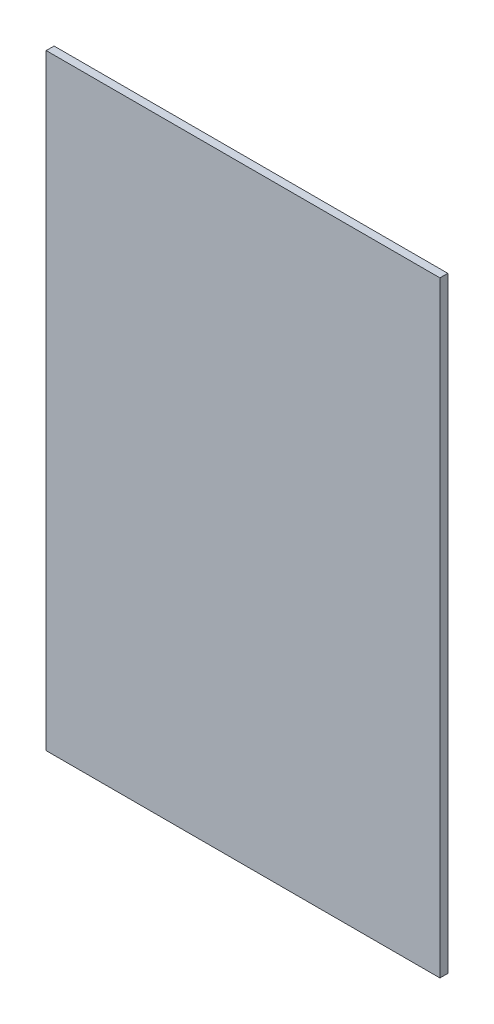
SolidWorks part; units mm, degrees
ref_plane "Front Plane" through (0, 0, 0) normal (0, 0, 1) x (1, 0, 0)
ref_plane "Top Plane" through (0, 0, 0) normal (0, 1, 0) x (1, 0, 0)
ref_plane "Right Plane" through (0, 0, 0) normal (1, 0, 0) x (0, 0, -1)
sketch "Sketch1" plane through (0, 0, 0) normal (0, 1, 0) x (1, 0, 0)
  line L1 (0, 0) -> (100, 0)
  line L2 (0, 0) -> (0, 2)
  line L3 (0, 2) -> (100, 2)
  line L4 (100, 0) -> (100, 2)
  dimension "D1" = 100
  dimension "D2" = 2
extrude "Boss-Extrude1" add sketch "Sketch1" along normal up to vertex (15 mm away) and the other way blind 139
